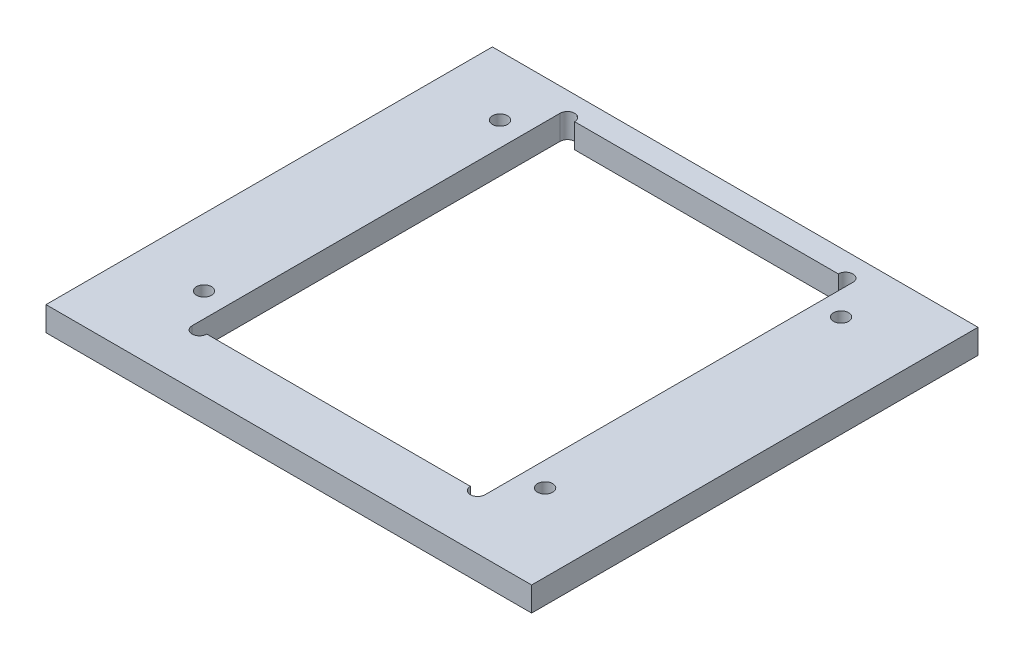
SolidWorks part; units mm, degrees
material "Thornel Mat VMA"
ref_plane "前视基准面" through (0, 0, 0) normal (0, 0, 1) x (1, 0, 0)
ref_plane "上视基准面" through (0, 0, 0) normal (0, 1, 0) x (1, 0, 0)
ref_plane "右视基准面" through (0, 0, 0) normal (1, 0, 0) x (0, 0, -1)
other "Configuration Table"
sketch "草图1" plane through (0, 0, 0) normal (0, 1, 0) x (1, 0, 0)
  line L1 (-30.05, 37.75) -> (30.05, 37.75)
  line L2 (-30.05, 37.75) -> (-30.05, -37.75)
  line L3 (-30.05, -37.75) -> (30.05, -37.75)
  line L4 (30.05, 37.75) -> (30.05, -37.75)
  line L5 (-30.05, 37.75) -> (30.05, -37.75) construction
  line L6 (-30.05, -37.75) -> (30.05, 37.75) construction
  line L7 (-48.7889, 42.6002) -> (50.8676, 42.6002)
  line L8 (-48.7889, 42.6002) -> (-48.7889, -49.0033)
  line L9 (-48.7889, -49.0033) -> (50.8676, -49.0033)
  line L10 (50.8676, 42.6002) -> (50.8676, -49.0033)
  point P0 (0, 0)
  dimension "D1" = 60.1
  dimension "D2" = 75.5
extrude "凸台-拉伸1" add sketch "草图1" along normal blind 5
sketch "草图2" plane through (0, 5, 0) normal (0, 1, 0) x (1, 0, 0)
  circle A0 centre (35, 30.3693) radius 1.55
  circle A1 centre (35, -30.3693) radius 1.55
  circle A2 centre (-35, -30.3693) radius 1.55
  circle A3 centre (-35, 30.3693) radius 1.55
  dimension "D1" = 3.1
extrude "切除-拉伸1" cut sketch "草图2" against normal blind 5
sketch "草图3" plane through (0, 5, 0) normal (0, 1, 0) x (1, 0, 0)
  line L0 (-30.05, -37.75) -> (30.05, -37.75) construction
  line L1 (30.05, 37.75) -> (-30.05, 37.75) construction
  line L2 (0, -59.2965) -> (0, 51.886) construction
  circle A0 centre (28.55, -37.75) radius 1.5
  circle A1 centre (28.55, 37.75) radius 1.5
  circle A2 centre (-28.55, 37.75) radius 1.5
  circle A3 centre (-28.55, -37.75) radius 1.5
  dimension "D1" = 3
extrude "切除-拉伸2" cut sketch "草图3" against normal blind 5
